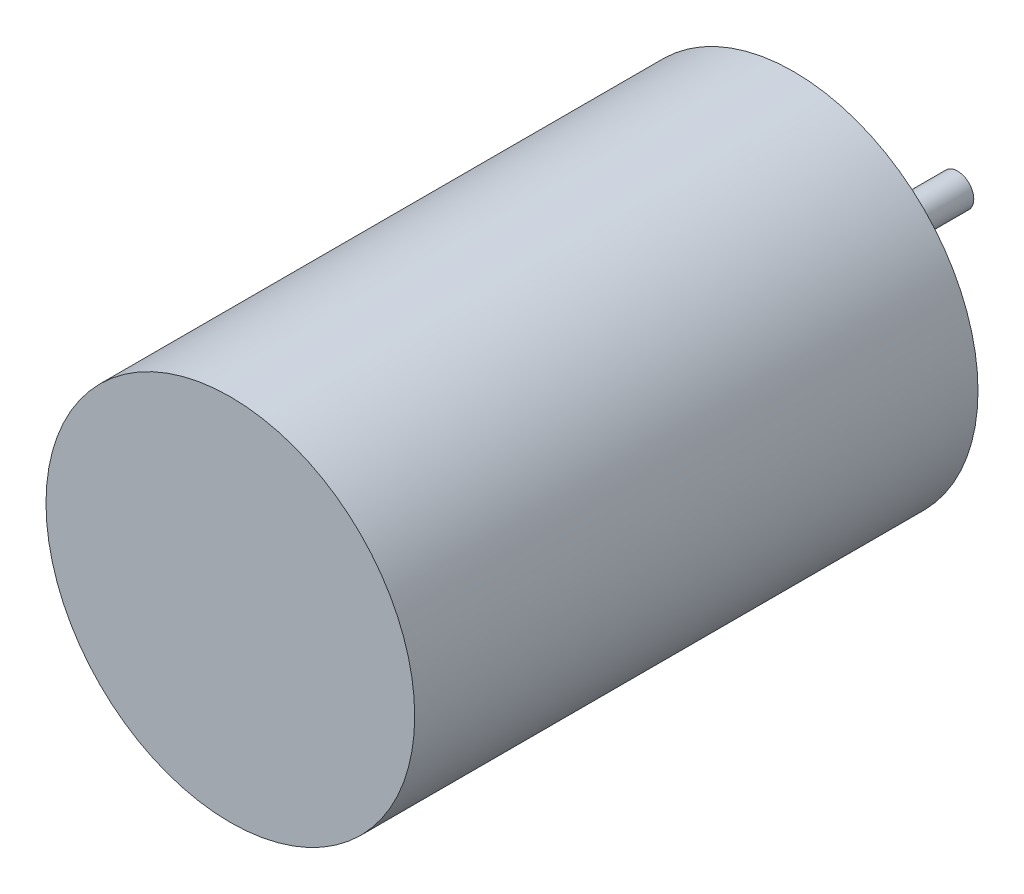
SolidWorks part; units mm, degrees
ref_plane "Front Plane" through (0, 0, 0) normal (0, 0, 1) x (1, 0, 0)
ref_plane "Top Plane" through (0, 0, 0) normal (0, 1, 0) x (1, 0, 0)
ref_plane "Right Plane" through (0, 0, 0) normal (1, 0, 0) x (0, 0, -1)
sketch "Sketch3" plane through (0, 0, 0) normal (0, 0, 1) x (1, 0, 0)
  circle A0 centre (0, 0) radius 18
extrude "Boss-Extrude1" add sketch "Sketch3" along normal blind 55
sketch "Sketch4" plane through (0, 0, 0) normal (0, 0, -1) x (-1, 0, 0)
  circle A0 centre (0, 0) radius 1.5875
extrude "Boss-Extrude2" add sketch "Sketch4" along normal blind 16
